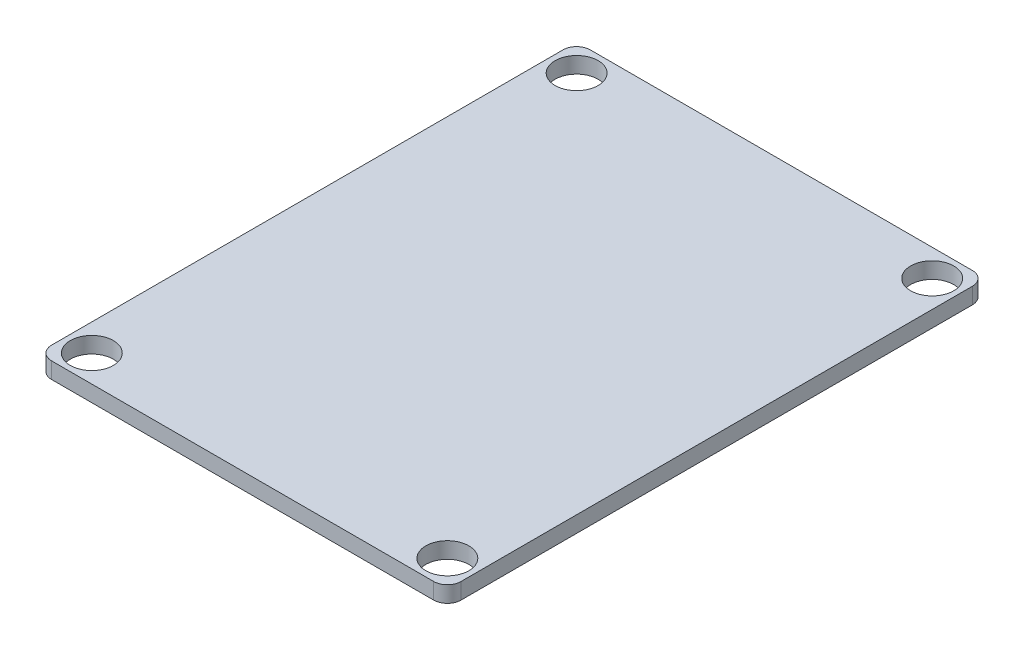
SolidWorks part; units mm, degrees
ref_plane "Front Plane" through (0, 0, 0) normal (0, 0, 1) x (1, 0, 0)
ref_plane "Top Plane" through (0, 0, 0) normal (0, 1, 0) x (1, 0, 0)
ref_plane "Right Plane" through (0, 0, 0) normal (1, 0, 0) x (0, 0, -1)
sketch "Sketch1" plane through (0, 0, 0) normal (0, 1, 0) x (1, 0, 0)
  line L1 (-38, -50) -> (38, -50)
  line L2 (-38, -50) -> (-38, 50)
  line L3 (-38, 50) -> (38, 50)
  line L4 (38, -50) -> (38, 50)
  line L5 (-38, -50) -> (38, 50) construction
  line L6 (-38, 50) -> (38, -50) construction
  point P0 (0, 0)
  dimension "D1" = 76
  dimension "D2" = 100
extrude "Boss-Extrude1" add sketch "Sketch1" along normal mid plane 3
fillet "Fillet1" radius 2.54 4 edges at (-38, 0, -50) (38, 0, -50) (-38, 0, 50) (38, 0, 50)
sketch "Sketch2" plane through (0, 1.5, 0) normal (0, 1, 0) x (1, 0, 0)
  line L0 (38, -47.46) -> (38, 47.46) construction
  line L1 (-33, -45) -> (33, -45) construction
  line L2 (-33, -45) -> (-33, 45) construction
  line L3 (-33, 45) -> (33, 45) construction
  line L4 (33, -45) -> (33, 45) construction
  line L5 (-33, -45) -> (33, 45) construction
  line L6 (-33, 45) -> (33, -45) construction
  line L7 (35.46, 50) -> (-35.46, 50) construction
  circle A0 centre (-33, 45) radius 4
  circle A1 centre (33, 45) radius 4
  circle A2 centre (33, -45) radius 4
  circle A3 centre (-33, -45) radius 4
  point P0 (0, 0)
  dimension "D3" = 8
  dimension "D1" = 5
  dimension "D2" = 5
extrude "Cut-Extrude1" cut sketch "Sketch2" against normal through all
